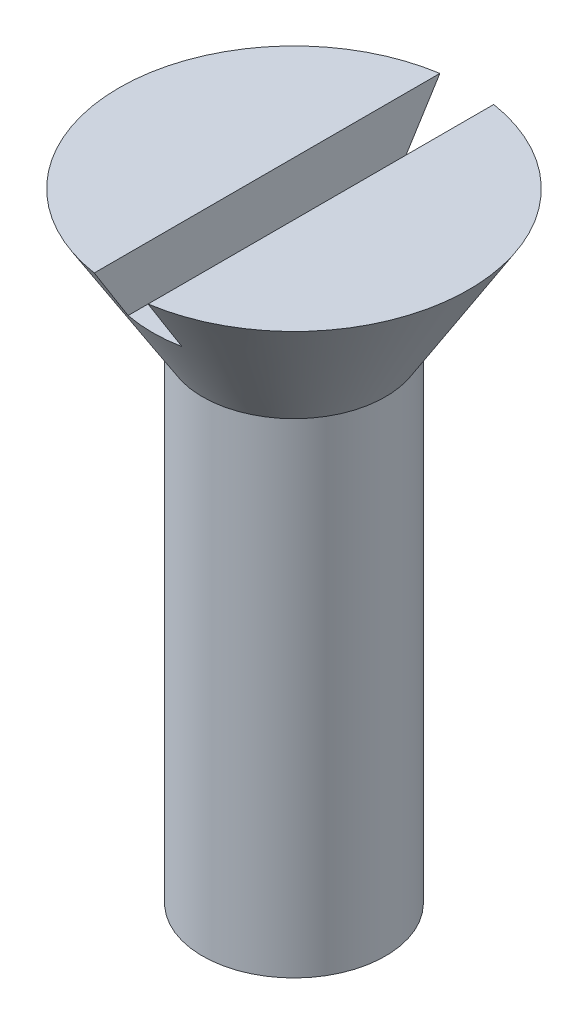
SolidWorks part; units mm, degrees
ref_plane "Front Plane" through (0, 0, 0) normal (0, 0, 1) x (1, 0, 0)
ref_plane "Top Plane" through (0, 0, 0) normal (0, 1, 0) x (1, 0, 0)
ref_plane "Right Plane" through (0, 0, 0) normal (1, 0, 0) x (0, 0, -1)
sketch "Sketch1" plane through (0, 0, 0) normal (0, 0, 1) x (1, 0, 0)
  line L1 (-6.5, 0) -> (-3.4, -5)
  line L2 (6.5, 0) -> (3.4, -5) construction
  line L3 (-3.4, -5) -> (-3.4, -23)
  line L4 (3.4, -5) -> (3.4, -23) construction
  line L5 (-3.4, -23) -> (0, -24.963)
  line L6 (0, -24.963) -> (3.4, -23) construction
  line L7 (-6.5, 0) -> (0, 0)
  line L8 (0, 0) -> (6.5, 0) construction
  line L9 (0, 0) -> (0, -24.963)
  point P4 (0, 0)
  dimension "D1" = 13
  dimension "D2" = 5
  dimension "D3" = 18
  dimension "D4" = 6.8
  dimension "D5" = 120
revolve "Revolve1" add sketch "Sketch1" angle 360 about L9
sketch "Sketch2" plane through (0, 0, 0) normal (0, 0, 1) x (1, 0, 0)
  line L0 (-1, 0) -> (1, 0)
  line L1 (6.5, 0) -> (-6.5, 0) construction
  line L2 (-1, 0) -> (-1, -2)
  line L3 (-1, -2) -> (1, -2)
  line L4 (1, -2) -> (1, 0)
  point P6 (0, 0)
  dimension "D1" = 2
extrude "Cut-Extrude1" cut sketch "Sketch2" against normal through all and the other way through all
